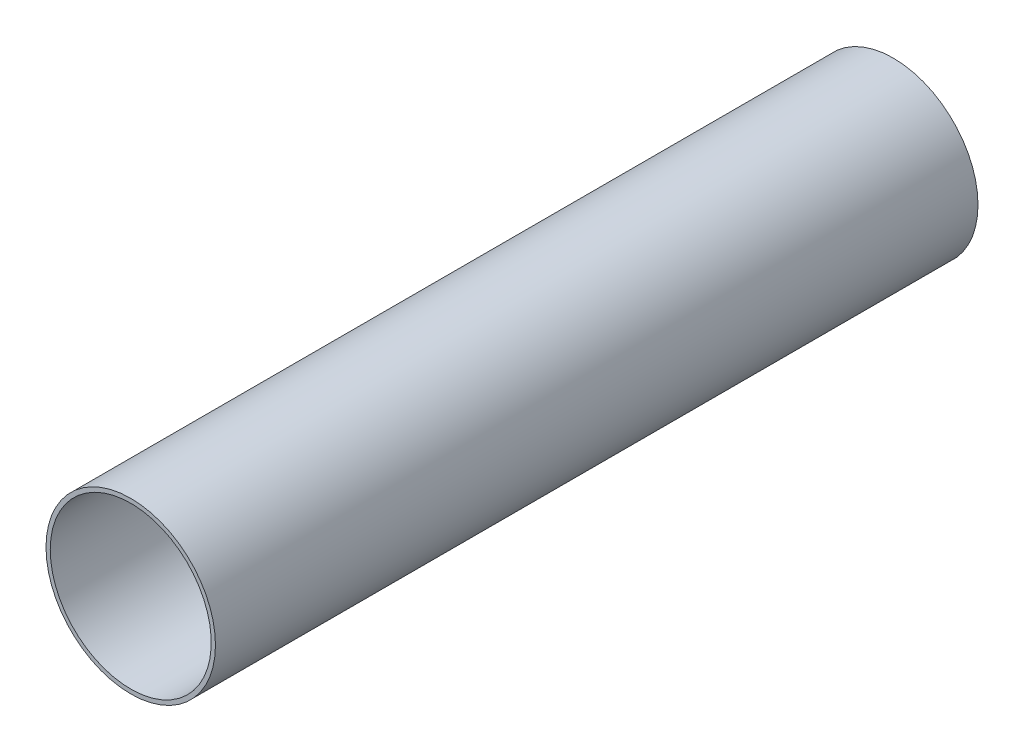
SolidWorks part; units mm, degrees
material "6061 合金"
ref_plane "前视基准面" through (0, 0, 0) normal (0, 0, 1) x (1, 0, 0)
ref_plane "上视基准面" through (0, 0, 0) normal (0, 1, 0) x (1, 0, 0)
ref_plane "右视基准面" through (0, 0, 0) normal (1, 0, 0) x (0, 0, -1)
sketch "草图1" plane through (0, 0, 0) normal (0, 0, 1) x (1, 0, 0)
  circle A0 centre (0, 0) radius 9.5
  circle A1 centre (0, 0) radius 10
  dimension "D1" = 19
  dimension "D2" = 20
extrude "凸台-拉伸1" add sketch "草图1" along normal blind 90
